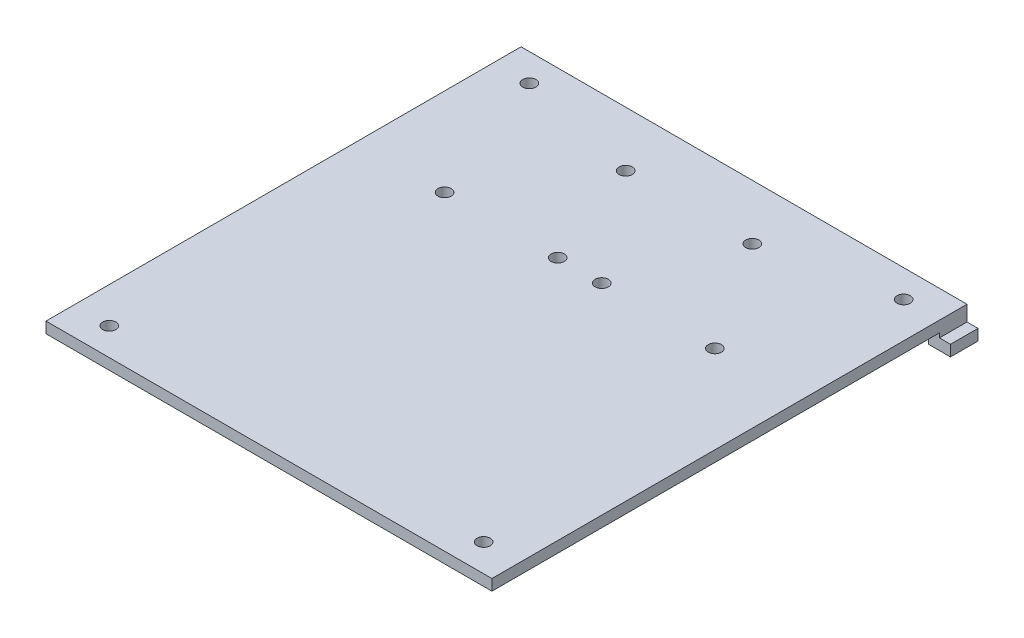
SolidWorks part; units mm, degrees
material "ABS"
ref_plane "正面" through (0, 0, 0) normal (0, 0, 1) x (1, 0, 0)
ref_plane "平面" through (0, 0, 0) normal (0, 1, 0) x (1, 0, 0)
ref_plane "右側面" through (0, 0, 0) normal (1, 0, 0) x (0, 0, -1)
sketch "ｽｹｯﾁ1" plane through (0, 0, 0) normal (0, 1, 0) x (1, 0, 0)
  line L1 (40.5, -43.15) -> (-40.5, -43.15)
  line L2 (40.5, -43.15) -> (40.5, 43.15)
  line L3 (40.5, 43.15) -> (-40.5, 43.15)
  line L4 (-40.5, -43.15) -> (-40.5, 43.15)
  line L5 (40.5, -43.15) -> (-40.5, 43.15) construction
  line L6 (40.5, 43.15) -> (-40.5, -43.15) construction
  point P0 (0, 0)
  dimension "D1" = 81
  dimension "D2" = 86.3
extrude "ﾎﾞｽ - 押し出し1" add sketch "ｽｹｯﾁ1" along normal blind 2
sketch "ｽｹｯﾁ2" plane through (0, 2, 0) normal (0, 1, 0) x (1, 0, 0)
  line L0 (-40.5, 43.15) -> (-40.5, -43.15) construction
  line L1 (40.5, -43.15) -> (40.5, 43.15) construction
  line L2 (-40.5, -43.15) -> (40.5, -43.15) construction
  line L3 (40.5, 43.15) -> (-40.5, 43.15) construction
  line L4 (-24.55, 43.15) -> (-24.55, -43.15) construction
  line L5 (24.55, 43.15) -> (24.55, -43.15) construction
  line L6 (0, 43.15) -> (0, -43.15) construction
  line L7 (-40.5, 33.15) -> (40.5, 33.15) construction
  line L8 (24.55, 13.3) -> (-24.55, 13.3) construction
  circle A0 centre (-34, -38.15) radius 1.2
  circle A1 centre (-34, 38.15) radius 1.2
  circle A2 centre (34, 38.15) radius 1.2
  circle A3 centre (34, -38.15) radius 1.2
  circle A4 centre (-24.55, 13.3) radius 1.2
  circle A5 centre (24.55, 13.3) radius 1.2
  circle A6 centre (-11.5, 33.15) radius 1.2
  circle A7 centre (11.5, 33.15) radius 1.2
  circle A8 centre (-4, 13.3) radius 1.2
  circle A9 centre (4, 13.3) radius 1.2
  dimension "D1" = 6.5
  dimension "D2" = 6.5
  dimension "D3" = 6.5
  dimension "D4" = 6.5
  dimension "D5" = 5
  dimension "D6" = 5
  dimension "D7" = 5
  dimension "D8" = 5
  dimension "D9" = 2.4
  dimension "D12" = 29.85
  dimension "D13" = 29.85
  dimension "D15" = 11.5
  dimension "D16" = 23
  dimension "D17" = 2.4
  dimension "D18" = 4
  dimension "D19" = 4
  dimension "D10" = 15.95
  dimension "D11" = 15.95
  dimension "D14" = 10
extrude "ｶｯﾄ - 押し出し1" cut sketch "ｽｹｯﾁ2" against normal blind 2
sketch "ｽｹｯﾁ3" plane through (0, 0, 0) normal (0, -1, 0) x (1, 0, 0)
  line L1 (-38.5, -38.15) -> (-40.5, -38.15)
  line L2 (-38.5, -38.15) -> (-38.5, -43.15)
  line L3 (-38.5, -43.15) -> (-40.5, -43.15)
  line L4 (-40.5, -38.15) -> (-40.5, -43.15)
  line L5 (-38.5, -38.15) -> (-40.5, -43.15) construction
  line L6 (-38.5, -43.15) -> (-40.5, -38.15) construction
  line L7 (38.5, -38.15) -> (40.5, -38.15)
  line L8 (38.5, -38.15) -> (38.5, -43.15)
  line L9 (38.5, -43.15) -> (40.5, -43.15)
  line L10 (40.5, -38.15) -> (40.5, -43.15)
  line L11 (38.5, -38.15) -> (40.5, -43.15) construction
  line L12 (38.5, -43.15) -> (40.5, -38.15) construction
  point P0 (-39.5, -40.65)
  point P6 (39.5, -40.65)
  dimension "D1" = 2
  dimension "D2" = 5
extrude "ﾎﾞｽ - 押し出し2" add sketch "ｽｹｯﾁ3" along normal blind 0.8
sketch "ｽｹｯﾁ4" plane through (0, -0.8, 0) normal (0, -1, 0) x (1, 0, 0)
  line L0 (-40.5, -40.65) -> (40.5, -40.65) construction
  line L1 (-40.5, -38.15) -> (-40.5, -43.15) construction
  line L2 (40.5, -43.15) -> (40.5, -38.15) construction
  line L4 (-42.5, -38.15) -> (-38.5, -38.15)
  line L5 (-42.5, -38.15) -> (-42.5, -43.15)
  line L6 (-42.5, -43.15) -> (-38.5, -43.15)
  line L7 (-38.5, -38.15) -> (-38.5, -43.15)
  line L8 (-42.5, -38.15) -> (-38.5, -43.15) construction
  line L9 (-42.5, -43.15) -> (-38.5, -38.15) construction
  line L10 (42.5, -38.15) -> (38.5, -38.15)
  line L11 (42.5, -38.15) -> (42.5, -43.15)
  line L12 (42.5, -43.15) -> (38.5, -43.15)
  line L13 (38.5, -38.15) -> (38.5, -43.15)
  line L14 (42.5, -38.15) -> (38.5, -43.15) construction
  line L15 (42.5, -43.15) -> (38.5, -38.15) construction
extrude "ﾎﾞｽ - 押し出し3" add sketch "ｽｹｯﾁ4" along normal blind 2
